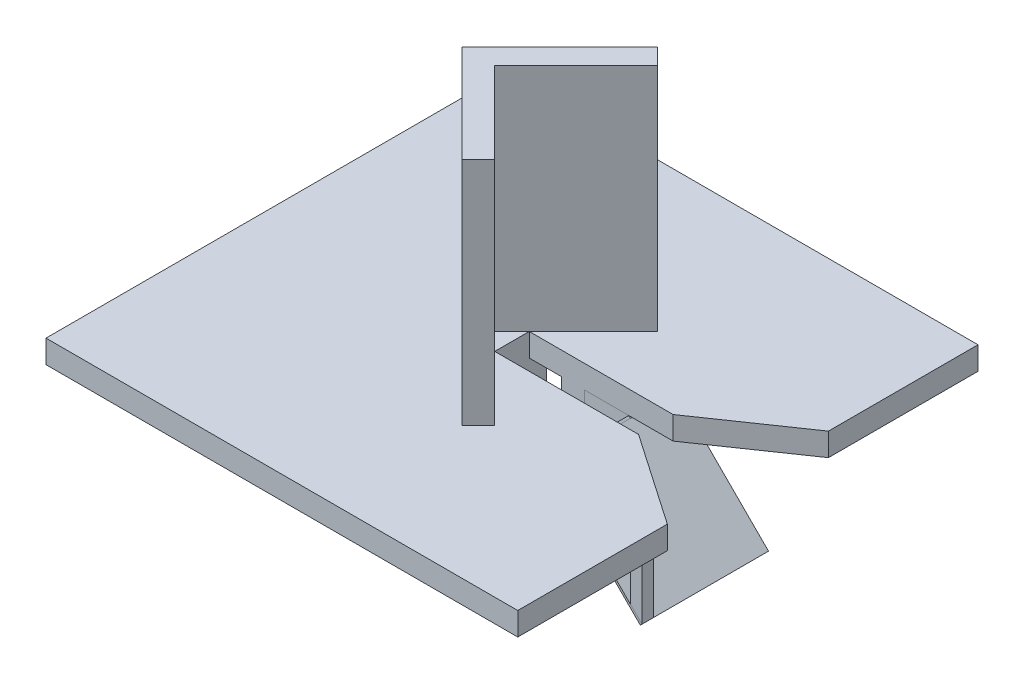
SolidWorks part; units mm, degrees
ref_plane "Front Plane" through (0, 0, 0) normal (0, 0, 1) x (1, 0, 0)
ref_plane "Top Plane" through (0, 0, 0) normal (0, 1, 0) x (1, 0, 0)
ref_plane "Right Plane" through (0, 0, 0) normal (1, 0, 0) x (0, 0, -1)
sketch "Sketch1" plane through (0, 0, 0) normal (0, 1, 0) x (1, 0, 0)
  line L0 (102.5, -35) -> (102.5, -100)
  line L1 (-102.5, 100) -> (102.5, 100)
  line L2 (-102.5, 100) -> (-102.5, -100)
  line L3 (-102.5, -100) -> (102.5, -100)
  line L4 (102.5, 100) -> (102.5, 35)
  line L6 (0, 7.5) -> (0, -7.5)
  line L8 (0, 7.5) -> (62.5, 7.5)
  line L9 (62.5, 7.5) -> (102.5, 35)
  line L10 (62.5, -7.5) -> (102.5, -35)
  line L11 (0, -7.5) -> (62.5, -7.5)
  point P0 (0, 0)
  point P11 (102.5, 0)
  point P14 (0, 0)
  dimension "D1" = 205
  dimension "D2" = 200
  dimension "D3" = 70
  dimension "D4" = 15
extrude "Boss-Extrude1" add sketch "Sketch1" along normal blind 10
sketch "Sketch2" plane through (0, 0, 0) normal (0, 1, 0) x (1, 0, 0)
  line L2 (0, 7.5) -> (-7.5, 0)
  line L3 (-7.5, 0) -> (27.8553, 35.3553)
  line L4 (-7.5, 0) -> (27.8553, -35.3553)
  line L5 (27.8553, -35.3553) -> (20.7843, -42.4264)
  line L6 (20.7843, -42.4264) -> (-14.5711, -7.0711)
  line L9 (-14.5711, 7.0711) -> (20.7843, 42.4264)
  line L10 (20.7843, 42.4264) -> (27.8553, 35.3553)
  line L11 (-14.5711, -7.0711) -> (-21.6421, 0)
  line L12 (-21.6421, 0) -> (-14.5711, 7.0711)
extrude "Boss-Extrude2" add sketch "Sketch2" along normal blind 110 contours L12 L11 L6 L5 L4 L2 L3 L10 L9
sketch "Sketch4" plane through (0, 0, 0) normal (1, 0, 0) x (0, 0, -1)
  line L2 (-7.5, -40) -> (7.5, -40)
  line L3 (-15, -40) -> (15, -40)
  line L4 (15, -40) -> (15, 0)
  line L5 (15, 0) -> (-15, 0)
  line L6 (-15, 0) -> (-15, -40)
  point P9 (0, -40)
  dimension "D2" = 30
extrude "Boss-Extrude3" add sketch "Sketch4" against normal blind 10 contours L5 L6 L3 L2 L4
sketch "Sketch6" plane through (0, 0, 0) normal (0, 1, 0) x (1, 0, 0)
  line L1 (14, 15) -> (14, 7.5)
  line L2 (0, 7.5) -> (62.5, 7.5) construction
  line L3 (0, -7.5) -> (0, 7.5)
  line L4 (14, 7.5) -> (24, 7.5)
  line L5 (14, 7.5) -> (14, 17.5)
  line L6 (14, 17.5) -> (24, 17.5)
  line L7 (24, 7.5) -> (24, 17.5)
  line L9 (14, -17.5) -> (24, -17.5)
  line L10 (24, -7.5) -> (24, -17.5)
  line L11 (14, -7.5) -> (24, -7.5)
  line L12 (14, -7.5) -> (14, -17.5)
  dimension "D2" = 10
  dimension "D3" = 10
extrude "Boss-Extrude4" add sketch "Sketch6" against normal blind 20 contours L11 L12 L9 L10 | L4 L7 L6 L5 L1
ref_plane "Plane1" through (24, 0, 0) normal (-1, 0, 0) x (0, 0, 1)
sketch "Sketch7" plane through (24, 0, 0) normal (-1, 0, 0) x (0, 0, 1)
  line L0 (17.5, -20) -> (17.5, -40)
  line L1 (-17.5, -20) -> (-17.5, -40)
  line L2 (-17.5, -40) -> (17.5, -40)
  line L3 (17.5, -20) -> (-17.5, -20)
  dimension "D1" = 20
extrude "Boss-Extrude6" add sketch "Sketch7" along normal blind 10 contours L3 L1 L2 L0
ref_plane "Plane3" through (0, 0, 7.5) normal (0, 0, 1) x (1, 0, 0)
sketch "Sketch13" plane through (0, 0, 7.5) normal (0, 0, 1) x (1, 0, 0)
  line L0 (24, 0) -> (62.5, 0)
  line L1 (24, -20) -> (43.25, 0)
  line L4 (43.25, 0) -> (43.9705, -0.6935)
  line L5 (43.9705, -0.6935) -> (24, -21.442)
  line L6 (24, -20) -> (24, -21.442)
  line L7 (24, -21.442) -> (24, -20)
  dimension "D1" = 1
  dimension "D2" = 90
extrude "Boss-Extrude8" add sketch "Sketch13" against normal blind 15 separate body contours L1 L6 L5 L4
sketch "Sketch15" plane through (0, 0, 7.5) normal (0, 0, 1) x (1, 0, 0)
  line L0 (24, -20) -> (24, 0)
  line L1 (24, 0) -> (43.25, 0)
  line L2 (62.5, 0) -> (24, 0) construction
  line L3 (43.25, 0) -> (24, -20)
extrude "Boss-Extrude10" add sketch "Sketch15" along normal blind 2 separate body
ref_plane "Plane4" through (0, 0, -7.5) normal (0, 0, 1) x (1, 0, 0)
sketch "Sketch16" plane through (0, 0, -7.5) normal (0, 0, 1) x (1, 0, 0)
  line L0 (24, -21.442) -> (24, 0)
  line L1 (24, 0) -> (43.25, 0)
  line L2 (24, 0) -> (62.5, 0) construction
  line L3 (43.25, 0) -> (24, -20)
extrude "Boss-Extrude12" add sketch "Sketch16" against normal blind 2 separate body contours L3 L1 L0
ref_plane "Plane5" through (43.9705, -0.6935, -7.5) normal (0, 0, 1) x (1, 0, 0)
sketch "Sketch19" plane through (0, 0, 7.5) normal (0, 0, 1) x (1, 0, 0)
  line L2 (83.9705, -40.6935) -> (43.9705, -0.6935)
  line L3 (83.9705, -40.6935) -> (83.2634, -41.4006)
  line L4 (83.2634, -41.4006) -> (43.2769, -1.4141)
  line L5 (43.9705, -0.6935) -> (24, -21.442) construction
  line L6 (43.2769, -1.4141) -> (43.9705, -0.6935)
  line L7 (43.9705, -0.6935) -> (43.2769, -1.4141)
  dimension "D3" = 1
extrude "Boss-Extrude13" add sketch "Sketch19" along normal blind 20 and the other way blind 35 contours L6 L4 L3 L2
ref_plane "Plane6" through (0, 0, 27.5) normal (0, 0, 1) x (1, 0, 0)
sketch "Sketch20" plane through (0, 0, 27.5) normal (0, 0, 1) x (1, 0, 0)
  line L0 (83.9705, -40.6935) -> (83.9705, 0)
  line L1 (83.9705, 0) -> (78.9705, 0)
  line L2 (78.9705, 0) -> (78.9705, -35.6935)
  line L3 (83.9705, -40.6935) -> (43.9705, -0.6935) construction
  line L4 (78.9705, -35.6935) -> (83.9705, -40.6935)
  dimension "D1" = 5
extrude "Boss-Extrude15" add sketch "Sketch20" against normal blind 5 separate body
ref_plane "Plane8" through (43.9705, -0.6935, -27.5) normal (0, 0, 1) x (1, 0, 0)
